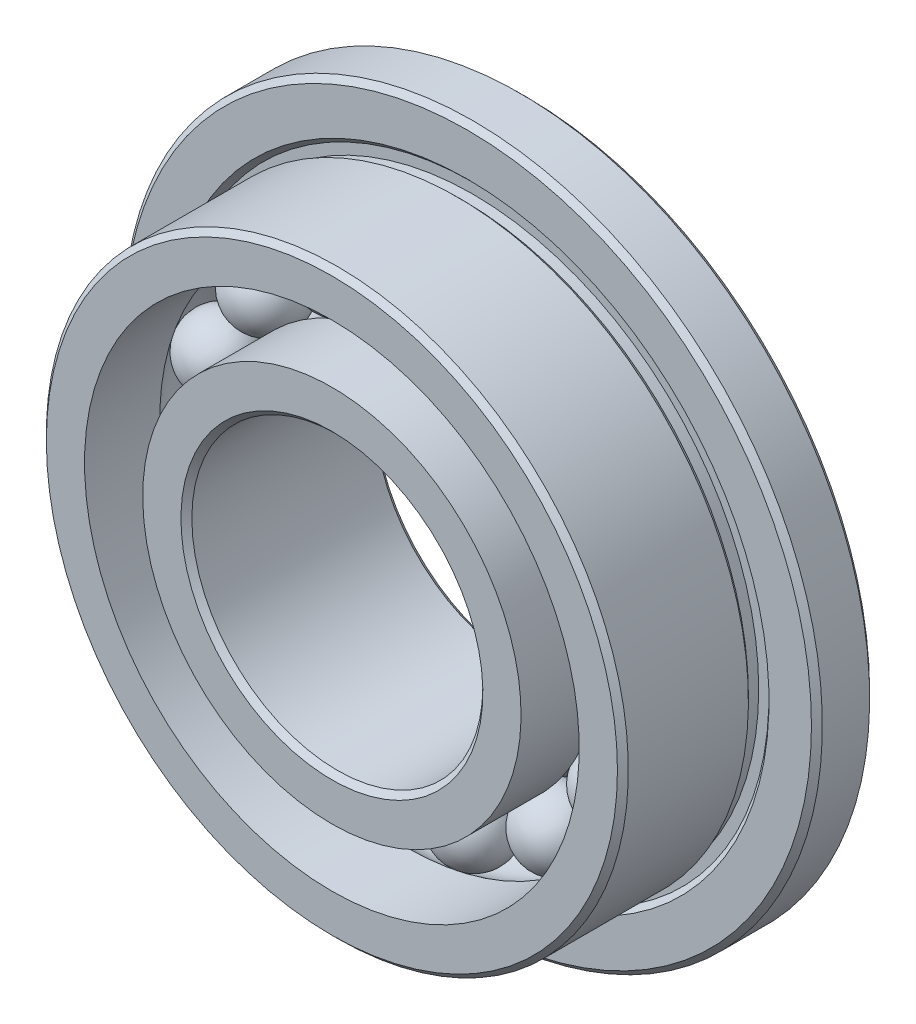
SolidWorks part; units mm, degrees
ref_plane "Front Plane" through (0, 0, 0) normal (0, 0, 1) x (1, 0, 0)
ref_plane "Top Plane" through (0, 0, 0) normal (0, 1, 0) x (1, 0, 0)
ref_plane "Right Plane" through (0, 0, 0) normal (1, 0, 0) x (0, 0, -1)
sketch "Sketch1" plane through (0, 0, 0) normal (1, 0, 0) x (0, 0, -1)
  line L0 (0, 3) -> (0, -3) construction
  line L1 (-1, 3) -> (1, 3) construction
  line L2 (0, 0) -> (1, 0) construction
  line L3 (1, 3.6) -> (1, -3.6) construction
  line L4 (1, -3.6) -> (0.4, -3.6) construction
  line L5 (1, 1.5) -> (0, 1.5) construction
  line L6 (1, 1.5) -> (1, -1.5) construction
  dimension "OD" = 6
  dimension "Width" = 2
  dimension "Flange Thickness" = 0.6
  dimension "ID" = 3
  dimension "Flange OD" = 7.2
sketch "Sketch2" plane through (0, 0, 0) normal (1, 0, 0) x (0, 0, -1)
  line L0 (1, 3.6) -> (0.4, 3.6)
  line L1 (0.4, 3.6) -> (0.4, 3.1061)
  line L2 (0.2939, 3) -> (-1, 3)
  line L3 (-1, 3) -> (-1, 2.55)
  line L4 (-1, 2.55) -> (-0.225, 2.55)
  line L5 (1, 3.6) -> (1, -3.6) construction
  line L6 (1, 2.55) -> (1, 3.6)
  line L7 (1, 1.5) -> (-1, 1.5)
  line L8 (-1, 1.5) -> (-1, 1.95)
  line L9 (-1, 1.95) -> (-0.225, 1.95)
  line L10 (1, 1.95) -> (1, 1.5)
  line L11 (0, 3) -> (0, 1.5) construction
  line L12 (-0.375, 2.25) -> (0.375, 2.25) construction
  line L13 (0.225, 2.55) -> (1, 2.55)
  line L14 (0.225, 1.95) -> (1, 1.95)
  line L15 (0.4, 3.1061) -> (0.453, 3.053)
  line L16 (0.453, 3.053) -> (0.453, 2.947)
  line L17 (0.453, 2.947) -> (0.347, 2.947)
  line L18 (0.347, 2.947) -> (0.2939, 3)
  line L19 (0.4, 3) -> (0.453, 2.947) construction
  line L20 (0.453, 3.053) -> (0.347, 2.947) construction
  line L21 (0.2939, 3) -> (0.4, 3) construction
  line L22 (0.4, 3) -> (0.4, 3.1061) construction
  circle A0 centre (0, 2.25) radius 0.375 construction
  arc A1 (-0.225, 2.55) -> (0.225, 2.55) centre (0, 2.25) cw
  arc A2 (-0.225, 1.95) -> (0.225, 1.95) centre (0, 2.25) ccw
  dimension "Ball Dia." = 0.75
  dimension "D2" = 135
  dimension "D3" = 0.15
  dimension "D4" = 0.6
  dimension "Race Thikness" = 0.45
revolve "Revolve1" add sketch "Sketch2" angle 360 about L2
fillet "Fillet1" radius 0.0563 3 edges at (0, -3.6, -1) (0, -3.6, -0.4) (0, -3, 1) profile chamfer
sketch "Sketch3" plane through (0, 0, 0) normal (0, 0, 1) x (1, 0, 0)
  line L0 (-1.5, 0) -> (1.5, 0) construction
  line L1 (-3, 0) -> (3, 0) construction
  point P5 (0, 0)
  dimension "ID2" = 3
  dimension "OD2" = 6
fillet "Fillet2" radius 0.0563 2 edges at (0, -1.5, -1) (0, -1.5, 1) profile chamfer
sketch "Sketch7" plane through (0, 0, 0) normal (0, 0, 1) x (1, 0, 0)
  line L0 (0, 2.625) -> (0, 1.875)
  line L1 (0, 3.6) -> (0, -3.6) construction
  line L2 (-0.4437, 2.625) -> (0, 0) construction
  line L3 (0, 0) -> (0.4437, 2.625) construction
  line L4 (0.4437, 2.625) -> (-0.4437, 2.625) construction
  circle A0 centre (0, 2.25) radius 0.375 construction
  circle A1 centre (0, 0) radius 2.625 construction
  circle A2 centre (0, 0) radius 1.875 construction
  arc A4 (0, 2.625) -> (0, 1.875) centre (0, 2.25) ccw
  dimension "D1" = 19.188
revolve "Revolve3" add sketch "Sketch7" angle 360 about L0
pattern_circular "CirPattern3" count 15 over 360 about axis through (0, 0, 0) along (0, 0, 1) of bodies 107
sketch "Sketch8" plane through (0, 0, 0) normal (1, 0, 0) x (0, 0, -1)
  line L0 (-1, 3) -> (1, 3) construction
  line L1 (1, 3) -> (1, 3.6) construction
  line L2 (-1, -3) -> (1, -3) construction
  line L3 (1, 3.6) -> (1, -3.6) construction
  dimension "D1" = 6
equation "\"Ball Dia.@Sketch2\" = ( \"OD@Sketch1\" - \"ID@Sketch1\" ) * .25"
equation "\"D3@Sketch2\"=\"Flange Thickness@Sketch1\"/4"
equation "\"D1@Fillet1\" = \"Race Thikness@Sketch2\" / 8"
equation "\"ID2@Sketch3\" = \"ID@Sketch1\""
equation "\"OD2@Sketch3\" = \"OD@Sketch1\""
equation "\"D1@Fillet2\" = \"Race Thikness@Sketch2\" / 8"
equation "\"D1@CirPattern3\"=360/\"D1@Sketch7\"-4"
equation "\"D4@Sketch2\" = ( \"OD@Sketch1\" - \"ID@Sketch1\" ) * .2"
